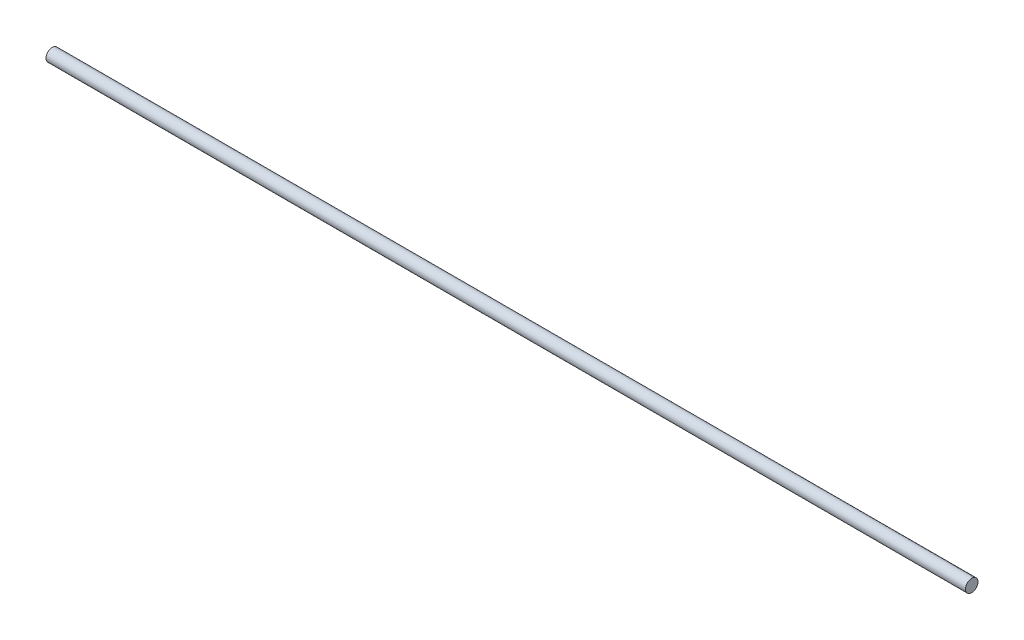
SolidWorks part; units mm, degrees
ref_plane "Front Plane" through (0, 0, 0) normal (0, 0, 1) x (1, 0, 0)
ref_plane "Top Plane" through (0, 0, 0) normal (0, 1, 0) x (1, 0, 0)
ref_plane "Right Plane" through (0, 0, 0) normal (1, 0, 0) x (0, 0, -1)
sketch "Sketch1" plane through (0, 0, 0) normal (0, 1, 0) x (1, 0, 0)
  line L0 (-350, 0) -> (350, 0)
  point P3 (0, 0)
  dimension "D1" = 700
sweep "Sweep1" add path "Sketch1" circular profile diameter 9.525 parameters "D3"=9.525
